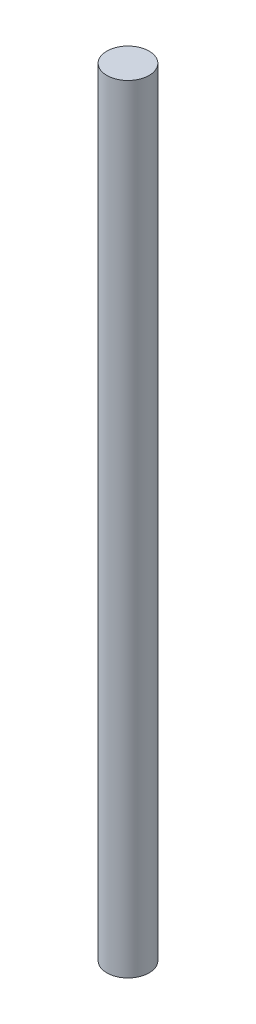
SolidWorks part; units mm, degrees
ref_plane "Ön Düzlem" through (0, 0, 0) normal (0, 0, 1) x (1, 0, 0)
ref_plane "Üst Düzlem" through (0, 0, 0) normal (0, 1, 0) x (1, 0, 0)
ref_plane "Sağ Düzlem" through (0, 0, 0) normal (1, 0, 0) x (0, 0, -1)
sketch "Çizim1" plane through (0, 0, 0) normal (0, 1, 0) x (1, 0, 0)
  circle A0 centre (0, 0) radius 5
  dimension "D1" = 10
extrude "Yükseklik-Ekstrüzyon1" add sketch "Çizim1" along normal blind 184
